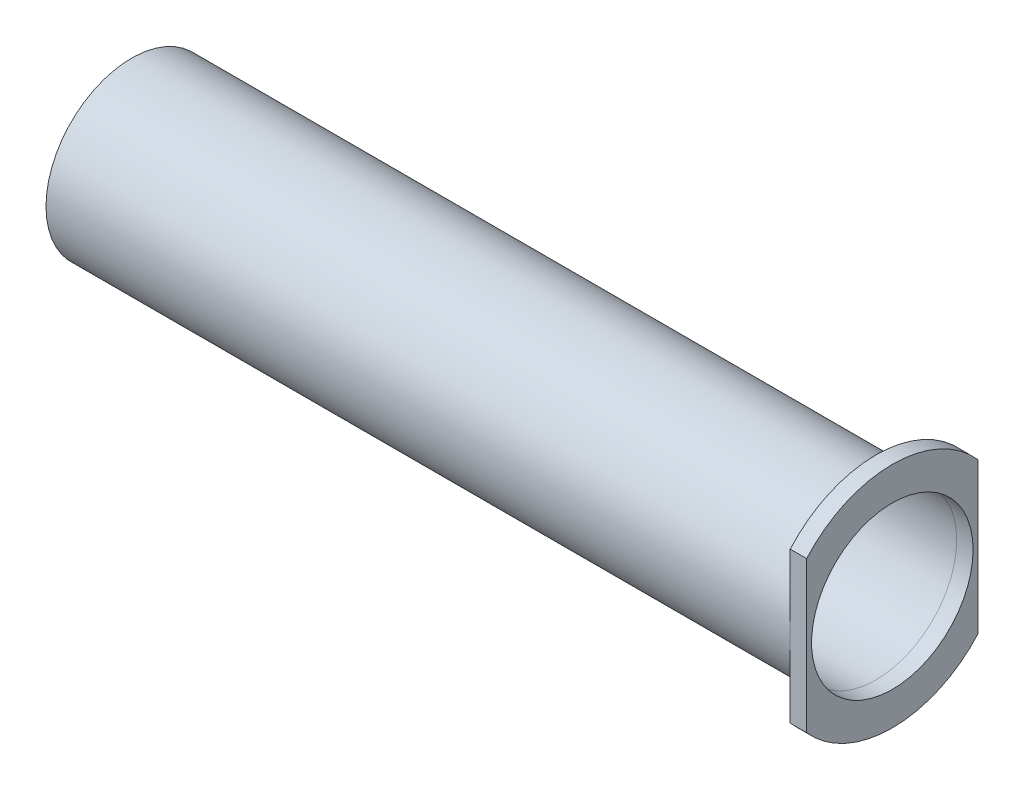
SolidWorks part; units mm, degrees
ref_plane "Płaszczyzna przednia" through (0, 0, 0) normal (0, 0, 1) x (1, 0, 0)
ref_plane "Płaszczyzna górna" through (0, 0, 0) normal (0, 1, 0) x (1, 0, 0)
ref_plane "Płaszczyzna prawa" through (0, 0, 0) normal (1, 0, 0) x (0, 0, -1)
sketch "Sketch1" plane through (0, 0, 0) normal (0, 0, 1) x (1, 0, 0)
  line L0 (0, 0) -> (157, 0)
  line L1 (5, 17.5) -> (157, 17.5)
  line L6 (5, 17.5) -> (5, 4.75)
  line L7 (157, 17.5) -> (157, 0)
  line L8 (5, 4.75) -> (0, 4.75)
  line L9 (0, 4.75) -> (0, 0)
  point P5 (-58.173, 17.5)
  point P9 (-58.0713, 0)
  point P10 (-56.6893, 0)
  point P11 (-61.7525, 0)
  point P12 (0, 0)
  point P13 (-61.3097, 0)
  point P14 (-61.7686, 0)
  point P15 (-58.0245, 0)
  dimension "D1" = 152
  dimension "D3" = 4.75
  dimension "D4" = 5
  dimension "D5" = 17.5
revolve "Revolve2" add sketch "Sketch1" angle 360 about L0
sketch "Sketch2" plane through (0, 0, 0) normal (-1, 0, 0) x (0, 0, 1)
  circle A0 centre (0, 0) radius 3.75
  circle A1 centre (0, 0) radius 4.75 construction
  dimension "D1" = 1
extrude "Cut-Extrude1" cut sketch "Sketch2" against normal blind 260 and the other way blind 45
sketch "Sketch3" plane through (157, 0, 0) normal (1, 0, 0) x (0, 0, -1)
  circle A0 centre (0, 0) radius 16.5
  circle A1 centre (0, 0) radius 17.5 construction
  dimension "D1" = 1
extrude "Cut-Extrude2" cut sketch "Sketch3" along a picked direction on the side against the normal blind 149
sketch "Sketch4" plane through (157, 0, 0) normal (1, 0, 0) x (0, 0, -1)
  line L0 (17.5, 0) -> (17.5, 27.7651)
  line L1 (17.5, 27.7651) -> (17.5, -27.7651)
  line L2 (-17.5, 0) -> (-17.5, 27.7651)
  line L3 (-17.5, 27.7651) -> (-17.5, -27.7651)
  circle A0 centre (0, 0) radius 32.82
  circle A1 centre (0, 0) radius 17.5 construction
  circle A2 centre (0, 0) radius 23.31
  circle M1 centre (0, 0) radius 16.5
  circle M2 centre (0, 0) radius 17.5
  dimension "D1" = 65.64
extrude "Boss-Extrude1" add sketch "Sketch4" along normal blind 3.35 separate body contours L0 A0 L2 M2 | L3 A0 L1 M2 | M2 M1
